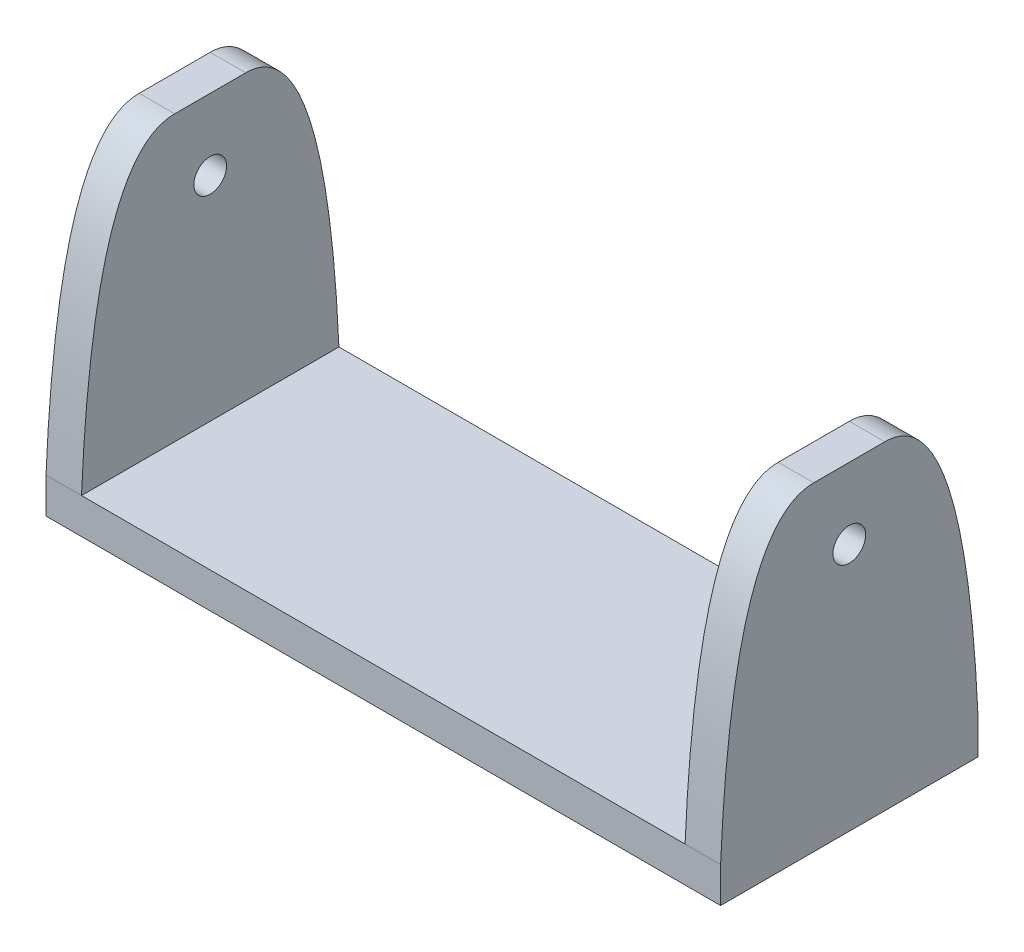
SolidWorks part; units mm, degrees
ref_plane "Front Plane" through (0, 0, 0) normal (0, 0, 1) x (1, 0, 0)
ref_plane "Top Plane" through (0, 0, 0) normal (0, 1, 0) x (1, 0, 0)
ref_plane "Right Plane" through (0, 0, 0) normal (1, 0, 0) x (0, 0, -1)
sketch "Sketch1" plane through (0, 0, 0) normal (0, 1, 0) x (1, 0, 0)
  line L1 (-32.5, 19.5) -> (32.5, 19.5) construction
  line L2 (-32.5, 19.5) -> (-32.5, -19.5) construction
  line L3 (-32.5, -19.5) -> (32.5, -19.5) construction
  line L4 (32.5, 19.5) -> (32.5, -19.5) construction
  line L5 (-38, 14.5) -> (38, 14.5)
  line L6 (-38, 14.5) -> (-38, -14.5)
  line L7 (-38, -14.5) -> (38, -14.5)
  line L8 (38, 14.5) -> (38, -14.5)
  line L9 (-38, 14.5) -> (38, -14.5) construction
  line L10 (-38, -14.5) -> (38, 14.5) construction
  point P4 (0, 0)
  dimension "D1" = 32.5
  dimension "D2" = 65
  dimension "D3" = 19.5
  dimension "D4" = 39
  dimension "D5" = 5.5
  dimension "D6" = 29
extrude "Boss-Extrude1" add sketch "Sketch1" along normal blind 4
sketch "Sketch2" plane through (0, 4, 0) normal (0, 1, 0) x (1, 0, 0)
  line L0 (-38, -14.5) -> (38, -14.5) construction
  line L1 (-38, 14.5) -> (-34, 14.5)
  line L2 (-38, 14.5) -> (-38, -14.5)
  line L3 (-38, -14.5) -> (-34, -14.5)
  line L4 (-34, 14.5) -> (-34, -14.5)
  line L6 (38, 14.5) -> (34, 14.5)
  line L7 (38, 14.5) -> (38, -14.5)
  line L8 (38, -14.5) -> (34, -14.5)
  line L9 (34, 14.5) -> (34, -14.5)
  point P12 (-38, 0)
  dimension "D1" = 4
  dimension "D2" = 4
extrude "Boss-Extrude2" add sketch "Sketch2" along normal blind 32
sketch "Sketch3" plane through (-38, 0, 0) normal (-1, 0, 0) x (0, 0, 1)
  line L1 (-14.5, 36) -> (14.5, 36) construction
  line L2 (-14.5, 0) -> (-14.5, 4) construction
  line L3 (-14.5, 36) -> (-14.5, 0) construction
  line L5 (-14.5, 4) -> (-13.053, 36) construction
  line L6 (-13.053, 36) -> (-4, 36) construction
  line L7 (0, 0) -> (0, 29.6078) construction
  line L9 (14.5, 4) -> (13.053, 36) construction
  line L10 (13.053, 36) -> (4, 36) construction
  line L11 (14.5, 4) -> (14.5, 36)
  line L12 (14.5, 36) -> (4, 36)
  line L13 (-4, 36) -> (-14.5, 36)
  line L14 (-14.5, 36) -> (-14.5, 4)
  spline S0 degree 2 poles (-14.5, 4) (-13.053, 36) (-4, 36) knots 0 0 0 1 1 1
  spline S1 degree 2 poles (14.5, 4) (13.053, 36) (4, 36) knots 0 0 0 1 1 1
  point P16 (0, 36)
  point P18 (0, 4)
  dimension "D1" = 4
  dimension "D2" = 4
extrude "Cut-Extrude1" cut sketch "Sketch3" against normal up to surface (76 mm away) up to face at (38, 18, 0)
sketch "Sketch4" plane through (34, 0, 0) normal (-1, 0, 0) x (0, 0, 1)
  line L0 (0, 0) -> (0, 41.0873) construction
  circle A0 centre (0, 28) radius 1.8431
  dimension "D1" = 28
extrude "Cut-Extrude2" cut sketch "Sketch4" against normal through all and the other way through all
